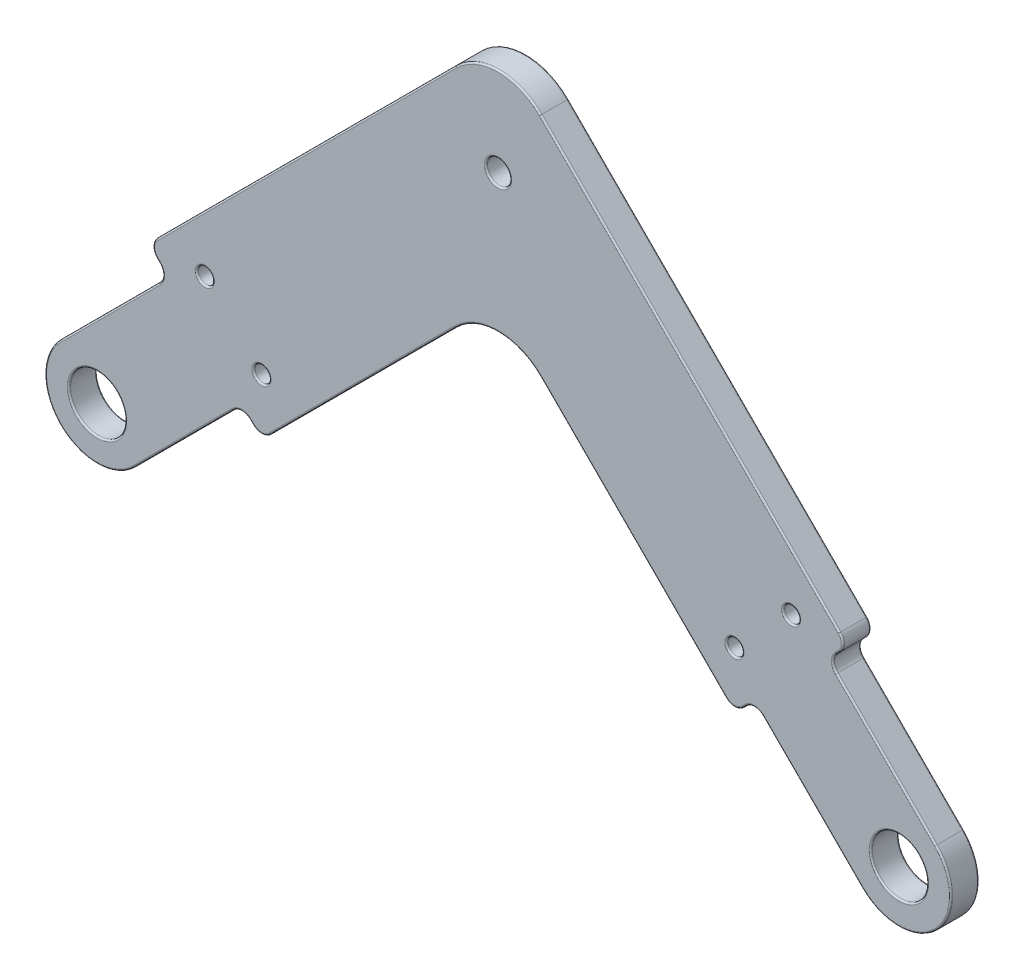
SolidWorks part; units mm, degrees
ref_plane "Front Plane" through (0, 0, 0) normal (0, 0, 1) x (1, 0, 0)
ref_plane "Top Plane" through (0, 0, 0) normal (0, 1, 0) x (1, 0, 0)
ref_plane "Right Plane" through (0, 0, 0) normal (1, 0, 0) x (0, 0, -1)
sketch "Sketch1" plane through (0, 0, 0) normal (0, 0, 1) x (1, 0, 0)
  line L0 (-100, 0) -> (100, 0) construction
  line L1 (-100, 0) -> (0, 100) construction
  line L2 (0, 100) -> (100, 0) construction
  line L3 (0, 0) -> (-50, 50) construction
  line L4 (-50, 50) -> (0, 0) construction
  line L5 (-40, 60) -> (40, 60) construction
  line L6 (0, 100) -> (0, 60) construction
  circle A0 centre (-100, 0) radius 20
  circle A1 centre (0, 0) radius 20
  circle A2 centre (100, 0) radius 20
  point P5 (0, 0)
  dimension "D5" = 40
  dimension "D1" = 200
  dimension "D2" = 90
  dimension "D3" = 90
  dimension "D4" = 80
sketch "Sketch2" plane through (0, 0, 0) normal (0, 0, 1) x (1, 0, 0)
  line L0 (-56.5165, 43.4835) -> (-40, 60) construction
  line L1 (-100, 0) -> (0, 100) construction
  line L2 (-40, 60) -> (40, 60) construction
  line L3 (40, 60) -> (86.565, 13.435) construction
  line L4 (0, 100) -> (100, 0) construction
  line L5 (-49.4454, 36.4124) -> (-35.8579, 50)
  line L6 (-35.8579, 50) -> (35.8579, 50)
  line L7 (35.8579, 50) -> (79.4939, 6.364)
  line L8 (-63.5876, 50.5546) -> (-44.1421, 70)
  line L9 (-44.1421, 70) -> (44.1421, 70)
  line L10 (44.1421, 70) -> (93.636, 20.5061)
  line L11 (-63.5876, 50.5546) -> (-49.4454, 36.4124)
  line L12 (93.636, 20.5061) -> (79.4939, 6.364)
  line L13 (81.9688, 8.8388) -> (95.4038, -4.5962)
  line L14 (91.1612, 18.0312) -> (104.5962, 4.5962)
  line L15 (75.9584, 9.8995) -> (90.1005, 24.0416) construction
  line L16 (0, 100) -> (0, 60) construction
  line L17 (-6, 70) -> (-3.4326, 85.5452)
  line L18 (6, 70) -> (3.4532, 85.4203)
  circle A0 centre (100, 0) radius 3.5
  circle A1 centre (100, 0) radius 10 construction
  arc A2 (95.4038, -4.5962) -> (104.5962, 4.5962) centre (100, 0) ccw
  circle A3 centre (100, 0) radius 0.5
  circle A4 centre (100, 0) radius 6.5 construction
  circle A5 centre (79.4939, 13.435) radius 1.8428
  circle A6 centre (86.565, 20.5061) radius 1.8428
  circle A7 centre (0, 60) radius 1.5
  circle A8 centre (0, 84.85) radius 1.5
  arc A9 (3.4532, 85.4203) -> (-3.4532, 85.4203) centre (0, 84.85) ccw
  circle A10 centre (0, 84.85) radius 3.5 construction
  circle A11 centre (-50, 50) radius 1.5
  dimension "D4" = 20
  dimension "D5" = 7
  dimension "D11" = 3
  dimension "D15" = 3
  dimension "D3" = 27.5
  dimension "D8" = 19
  dimension "D9" = 5
  dimension "D10" = 5
  dimension "5" = 5
  dimension "D12" = 14.85
  dimension "D7" = 6
  dimension "D14" = 6
  dimension "D1" = 10
  dimension "D2" = 10
  dimension "D6" = 3
  dimension "D13" = 2
sketch "Sketch3" plane through (0, 0, 0) normal (0, 0, 1) x (1, 0, 0)
  line L0 (-100, 0) -> (100, 0) construction
  line L1 (-14.1421, 19.799) -> (-12.7279, 21.2132) construction
  line L2 (-21.2132, 12.7279) -> (-19.799, 14.1421) construction
  line L3 (-50, 50) -> (-48.9393, 48.9393) construction
  line L5 (-79.4939, 6.364) -> (-50, 35.8579)
  line L6 (-50, 35.8579) -> (-20.5061, 6.364)
  line L7 (-93.636, 20.5061) -> (-50, 64.1421)
  line L8 (-50, 64.1421) -> (-6.364, 20.5061)
  line L9 (-81.6799, 4.1779) -> (-50, 35.8579) construction
  line L10 (-95.8221, 18.3201) -> (-50, 64.1421) construction
  line L11 (-93.636, 20.5061) -> (-91.1612, 18.0312)
  line L12 (-20.5061, 6.364) -> (-18.0312, 8.8388)
  line L13 (-81.9688, 8.8388) -> (-95.4038, -4.5962)
  line L14 (-91.1612, 18.0312) -> (-104.5962, 4.5962)
  line L15 (-18.0312, 8.8388) -> (-4.5962, -4.5962)
  line L16 (-8.8388, 18.0312) -> (4.5962, 4.5962)
  line L17 (-88.751, 11.249) -> (-50, 50) construction
  line L18 (-87.2721, 21.2132) -> (-85.8579, 19.799) construction
  line L19 (-8.8388, 18.0312) -> (-6.364, 20.5061)
  line L20 (-81.9688, 8.8388) -> (-79.4939, 6.364)
  line L21 (-51.0607, 48.9393) -> (-50, 50) construction
  line L23 (-50, 50) -> (-13.435, 13.435) construction
  line L24 (-80.201, 14.1421) -> (-78.7868, 12.7279) construction
  circle A1 centre (-100, 0) radius 3.5
  circle A3 centre (0, 0) radius 3.5
  arc A4 (-4.5962, -4.5962) -> (4.5962, 4.5962) centre (0, 0) ccw
  arc A5 (-104.5962, 4.5962) -> (-95.4038, -4.5962) centre (-100, 0) ccw
  circle A6 centre (-86.565, 20.5061) radius 1
  circle A7 centre (0, 0) radius 6.5 construction
  circle A8 centre (-100, 0) radius 6.5 construction
  circle A9 centre (-79.4939, 13.435) radius 1
  circle A10 centre (-20.5061, 13.435) radius 1
  circle A11 centre (-13.435, 20.5061) radius 1
  circle A12 centre (-50, 50) radius 1.5 construction
  circle A13 centre (-50, 50) radius 1.5
  dimension "D2" = 7
  dimension "D9" = 2
  dimension "D7" = 19
  dimension "D8" = 19
  dimension "D12" = 5
  dimension "D13" = 5
  dimension "D14" = 5
  dimension "D15" = 5
  dimension "D3" = 3
  dimension "D4" = 3
  dimension "D5" = 10
  dimension "D6" = 10
sketch "Sketch4" plane through (0, 0, 0) normal (0, 0, 1) x (1, 0, 0)
  line L1 (57.5, 96.35) -> (57.5, 86.35)
  line L2 (57.5, 86.35) -> (44.1421, 70)
  line L3 (44.1421, 70) -> (-44.1421, 70)
  line L4 (-44.1421, 70) -> (-57.5, 86.35)
  line L5 (-57.5, 86.35) -> (-57.5, 96.35)
  line L7 (-57.5, 96.35) -> (57.5, 96.35)
  line L8 (-4, 60) -> (-4, 70)
  line L9 (4, 60) -> (4, 70)
  line L10 (-22.4799, 87.85) -> (22.5201, 87.85) construction
  line L11 (-22.4799, 92.35) -> (22.5201, 92.35)
  line L12 (-22.4799, 83.35) -> (22.5201, 83.35)
  circle A0 centre (0, 60) radius 1.5 construction
  circle A1 centre (0, 60) radius 1.5
  arc A2 (-4, 60) -> (4, 60) centre (0, 60) ccw
  circle A3 centre (0, 60) radius 4 construction
  arc A4 (-22.4799, 92.35) -> (-22.4799, 83.35) centre (-22.4799, 87.85) ccw
  arc A5 (22.5201, 83.35) -> (22.5201, 92.35) centre (22.5201, 87.85) ccw
  circle A6 centre (0, 84.85) radius 1.5 construction
  point P0 (0, 96.35)
  point P22 (0.0201, 87.85)
  dimension "D1" = 115
  dimension "D2" = 10
  dimension "D4" = 45
  dimension "D5" = 9
  dimension "D6" = 45
  dimension "D7" = 4
  dimension "D3" = 2.5
extrude "Boss-Extrude1" add sketch "Sketch3" along normal blind 3.5
fillet "Fillet1" radius 7.5 2 edges at (-50, 35.8579, 1.75) (-50, 64.1421, 1.75)
fillet "Fillet3" radius 1.5 8 edges at (-81.9688, 8.8388, 1.75) (-79.4939, 6.364, 1.75) (-91.1612, 18.0312, 1.75) (-93.636, 20.5061, 1.75) (-6.364, 20.5061, 1.75) (-8.8388, 18.0312, 1.75) (-18.0312, 8.8388, 1.75) (-20.5061, 6.364, 1.75)
fillet "Fillet4" radius 0.2 62 edges at (-48.5, 50, 0) (-48.5, 50, 3.5) (-12.435, 20.5061, 0) (-12.435, 20.5061, 3.5) (-19.5061, 13.435, 0) (-19.5061, 13.435, 3.5) (-78.4939, 13.435, 0) (-78.4939, 13.435, 3.5) (-85.565, 20.5061, 0) (-85.565, 20.5061, 3.5) (3.5, 0, 0) (3.5, 0, 3.5) (-96.5, 0, 0) (-96.5, 0, 3.5) (-80.7313, 7.6014, 0) (-66.8683, 18.9896, 0) (-33.1317, 18.9896, 0) (-19.2687, 7.6014, 0) (-10.7834, 1.591, 0) (4.5962, -4.5962, 0) (-1.591, 10.7834, 0) (-7.6014, 19.2687, 0) (-26.0607, 40.2028, 0) (-73.9393, 40.2028, 0) (-92.3986, 19.2687, 0) (-98.409, 10.7834, 0) (-104.5962, -4.5962, 0) (-89.2166, 1.591, 0) (-80.7313, 7.6014, 3.5) (-66.8683, 18.9896, 3.5) (-33.1317, 18.9896, 3.5) (-19.2687, 7.6014, 3.5) (-10.7834, 1.591, 3.5) (4.5962, -4.5962, 3.5) (-1.591, 10.7834, 3.5) (-7.6014, 19.2687, 3.5) (-73.9393, 40.2028, 3.5) (-92.3986, 19.2687, 3.5) (-98.409, 10.7834, 3.5) (-104.5962, -4.5962, 3.5) (-89.2166, 1.591, 3.5) (-50, 61.0355, 0) (-50, 61.0355, 3.5) (-50, 32.7513, 0) (-50, 32.7513, 3.5) (-20.5061, 6.9853, 0) (-6.9853, 20.5061, 0) (-93.0147, 20.5061, 0) (-79.4939, 6.9853, 0) (-20.5061, 6.9853, 3.5) (-6.9853, 20.5061, 3.5) (-93.0147, 20.5061, 3.5) (-79.4939, 6.9853, 3.5) (-81.9688, 8.2175, 0) (-81.9688, 8.2175, 3.5) (-91.7825, 18.0312, 0) (-91.7825, 18.0312, 3.5) (-8.2175, 18.0312, 0) (-8.2175, 18.0312, 3.5) (-18.0312, 8.2175, 0) (-18.0312, 8.2175, 3.5) (-26.0607, 40.2028, 3.5)
